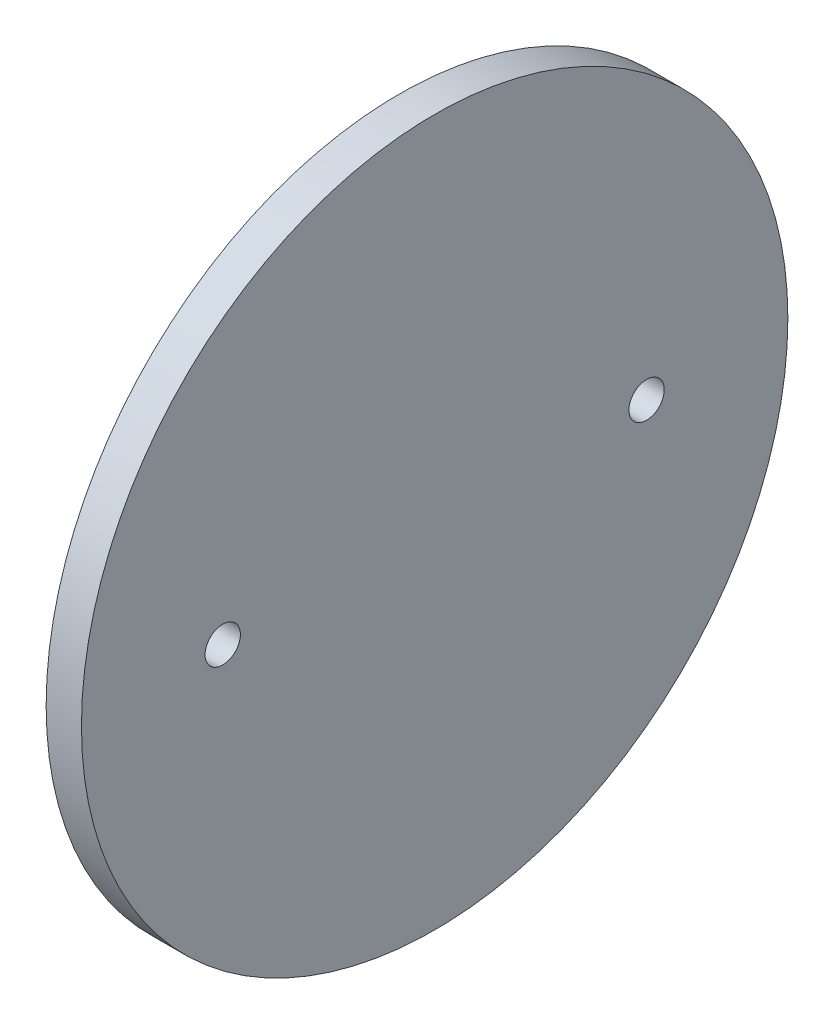
SolidWorks part; units mm, degrees
material "CMR DEFAULT - CHANGE MATERIAL"
ref_plane "XY PLANE - TOP" through (0, 0, 0) normal (0, 0, 1) x (1, 0, 0)
ref_plane "XZ PLANE - SIDE" through (0, 0, 0) normal (0, 1, 0) x (1, 0, 0)
ref_plane "YZ PLANE - FRONT" through (0, 0, 0) normal (1, 0, 0) x (0, 0, -1)
sketch "Sketch1" plane through (0, 0, 0) normal (1, 0, 0) x (0, 0, -1)
  line L0 (88.5065, 0) -> (-88.5065, 0) construction
  line L1 (-38.1, 0) -> (0, 0) construction
  line L2 (0, 0) -> (38.1, 0) construction
  circle A0 centre (0, 0) radius 63.5
  circle A2 centre (38.1, 0) radius 3.175
  circle A3 centre (-38.1, 0) radius 3.175
  dimension "D1" = 127
  dimension "D2" = 6.35
  dimension "D3" = 38.1
  dimension "D4" = 38.1
extrude "Boss-Extrude1" add sketch "Sketch1" along normal blind 6.35
